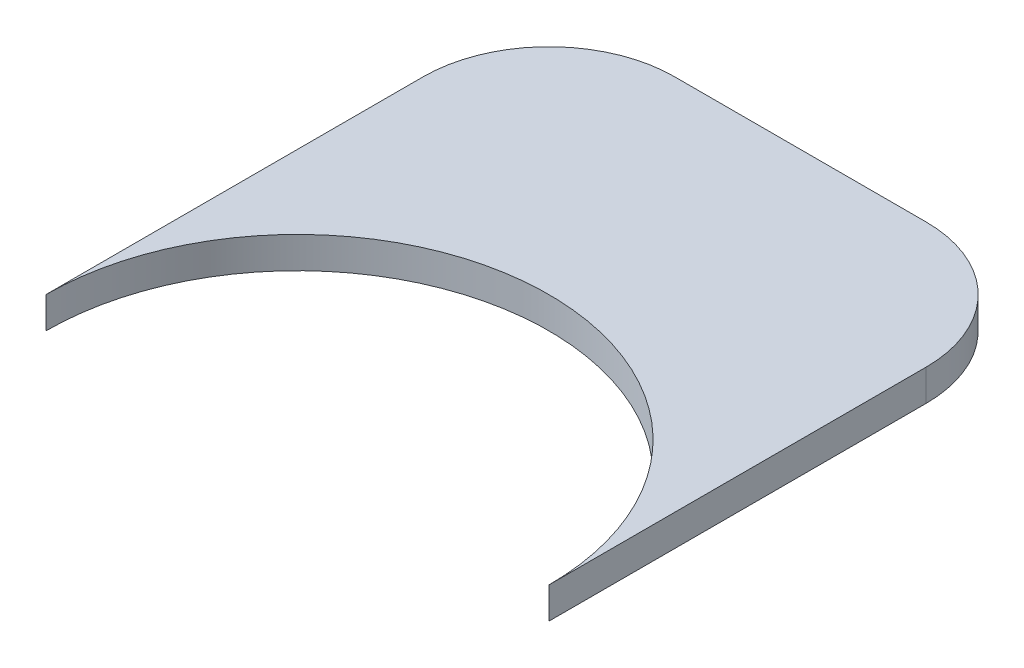
SolidWorks part; units mm, degrees
ref_plane "Front Plane" through (0, 0, 0) normal (0, 0, 1) x (1, 0, 0)
ref_plane "Top Plane" through (0, 0, 0) normal (0, 1, 0) x (1, 0, 0)
ref_plane "Right Plane" through (0, 0, 0) normal (1, 0, 0) x (0, 0, -1)
sketch "Sketch1" plane through (0, 0, 0) normal (0, 1, 0) x (1, 0, 0)
  line L2 (-12.7, -9.525) -> (-12.7, 9.525)
  line L3 (-6.35, 15.875) -> (6.35, 15.875)
  line L4 (12.7, -9.525) -> (12.7, 9.525)
  arc A0 (12.7, -9.525) -> (-12.7, -9.525) centre (0, -9.525) ccw
  arc A1 (6.35, 15.875) -> (12.7, 9.525) centre (6.35, 9.525) cw
  arc A2 (-12.7, 9.525) -> (-6.35, 15.875) centre (-6.35, 9.525) cw
  point P0 (12.7, 0)
  point P7 (0, 0)
  point P8 (0, -14.4431)
  point P10 (-8.6304, -12.7)
  point P11 (0, 0)
  point P16 (-12.7, 15.875)
  dimension "D2" = 25.4
  dimension "D1" = 12.7
  dimension "D3" = 6.35
extrude "Boss-Extrude1" add sketch "Sketch1" along normal blind 1.5875
